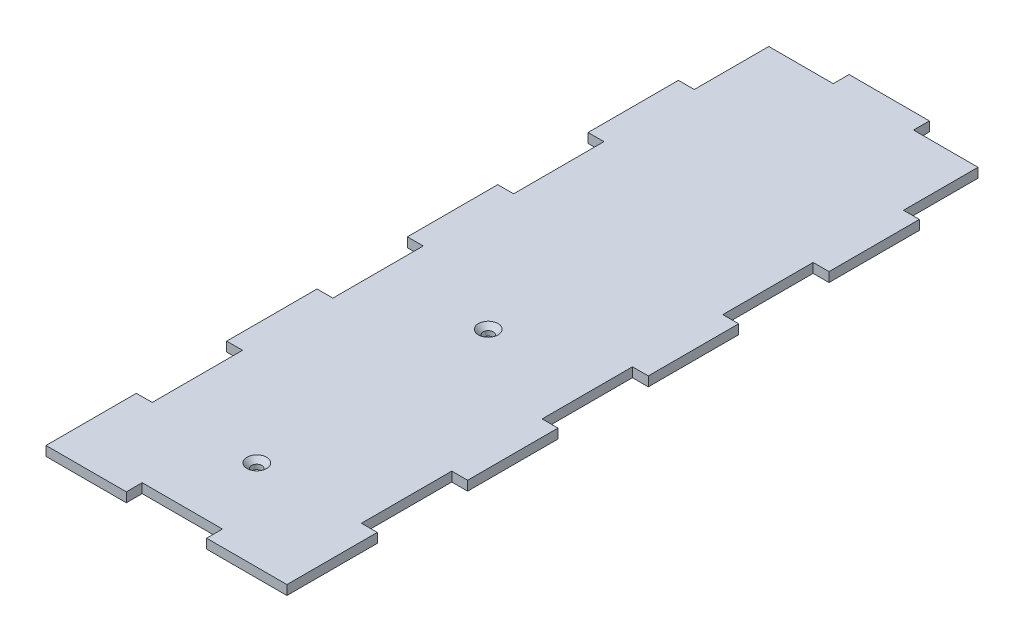
SolidWorks part; units mm, degrees
ref_plane "Front Plane" through (0, 0, 0) normal (0, 0, 1) x (1, 0, 0)
ref_plane "Top Plane" through (0, 0, 0) normal (0, 1, 0) x (1, 0, 0)
ref_plane "Right Plane" through (0, 0, 0) normal (1, 0, 0) x (0, 0, -1)
sketch "Sketch1" plane through (0, 0, 0) normal (0, 1, 0) x (1, 0, 0)
  line L0 (-38, -114) -> (-12.6667, -114)
  line L1 (-38, -114) -> (38, -114) construction
  line L2 (-38, -114) -> (-38, 114) construction
  line L3 (-38, 114) -> (38, 114) construction
  line L4 (38, -114) -> (38, 114) construction
  line L5 (0, 114) -> (0, -114) construction
  line L6 (-38, 0) -> (38, 0) construction
  line L7 (-12.6667, -114) -> (-12.6667, -109)
  line L8 (-12.6667, -109) -> (0, -109)
  line L9 (-38, -114) -> (-38, -85.5)
  line L13 (-38, -85.5) -> (-33, -85.5)
  line L14 (-33, -85.5) -> (-33, -57)
  line L15 (-33, -57) -> (-38, -57)
  line L20 (0, -109) -> (0, 114)
  line L22 (-33, 109) -> (-33, 85.5)
  line L23 (-33, 109) -> (-12.6667, 109)
  line L24 (-38, -57) -> (-38, -28.5)
  line L25 (-38, -28.5) -> (-33, -28.5)
  line L26 (-33, -28.5) -> (-33, 0)
  line L27 (-33, 0) -> (-38, 0)
  line L28 (-38, 0) -> (-38, 28.5)
  line L29 (-38, 28.5) -> (-33, 28.5)
  line L30 (-33, 28.5) -> (-33, 57)
  line L31 (-33, 57) -> (-38, 57)
  line L32 (-38, 57) -> (-38, 85.5)
  line L33 (-38, 85.5) -> (-33, 85.5)
  line L34 (-12.6667, 109) -> (-12.6667, 114)
  line L35 (-12.6667, 114) -> (0, 114)
  point P56 (0, 0)
  dimension "D1" = 228
  dimension "D2" = 76
  dimension "D4" = 5
  dimension "D6" = 5
  dimension "D5" = 28.5
  dimension "D8" = 28.5
  dimension "D9" = 28.5
  dimension "D10" = 28.5
  dimension "D11" = 28.5
  dimension "D12" = 28.5
  dimension "D3" = 12.6667
  dimension "D7" = 5
  dimension "D13" = 28.5
extrude "Boss-Extrude1" add sketch "Sketch1" along normal blind 3
mirror "Mirror1" about plane through (0, 3, 109) normal (-1, 0, 0) of "Boss-Extrude1"
sketch "Sketch2" plane through (0, 3, 0) normal (0, 1, 0) x (1, 0, 0)
  line L0 (-38, -85.5) -> (38, -85.5) construction
  line L1 (-38, -85.5) -> (-38, -114) construction
  line L2 (38, -85.5) -> (38, -114) construction
  line L3 (0, -85.5) -> (0, -12.5) construction
  line L4 (-33, -85.5) -> (-38, -85.5) construction
  circle A0 centre (0, -85.5) radius 1.6
  circle A1 centre (0, -12.5) radius 1.6
  dimension "D2" = 3.2
  dimension "D1" = 73
extrude "Cut-Extrude1" cut sketch "Sketch2" against normal through all
chamfer "Chamfer1" distance 1.5 angle 45 2 edges at (0, 3, 87.1) (0, 3, 14.1)
equation "\"3mm akryyli\"= 3mm"
equation "\"5mm akryyli\"= 5mm"
equation "\"D4@Sketch1\"=\"5mm akryyli\""
equation "\"D6@Sketch1\"=\"5mm akryyli\""
equation "\"D7@Sketch1\"=\"5mm akryyli\""
